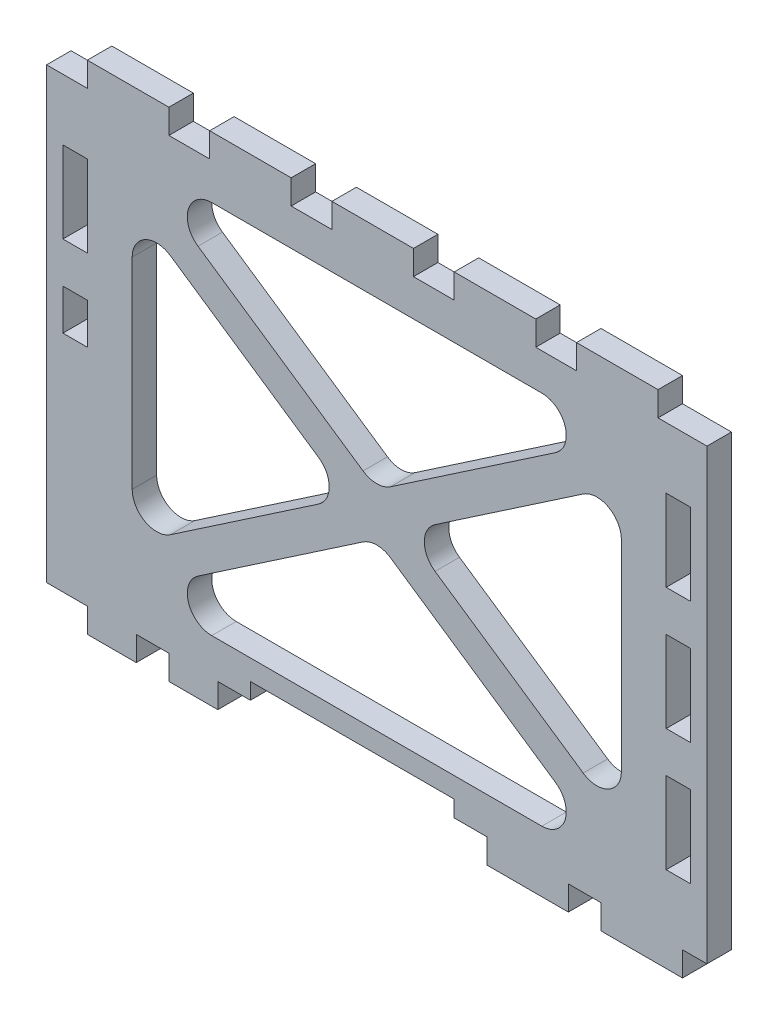
SolidWorks part; units mm, degrees
material "轻木"
ref_plane "前视基准面" through (0, 0, 0) normal (0, 0, 1) x (1, 0, 0)
ref_plane "上视基准面" through (0, 0, 0) normal (0, 1, 0) x (1, 0, 0)
ref_plane "右视基准面" through (0, 0, 0) normal (1, 0, 0) x (0, 0, -1)
sketch "草图1" plane through (0, 0, 0) normal (0, 0, 1) x (1, 0, 0)
  line L0 (-10.5, 27.5) -> (-10.5, 30.5)
  line L1 (-40.5, 27.5) -> (-35.5, 27.5)
  line L2 (-40.5, 27.5) -> (-40.5, -27.5)
  line L3 (-40.5, -27.5) -> (-35.5, -27.5)
  line L6 (35.5, 5) -> (35.5, -5)
  line L8 (-25.5, 27.5) -> (-25.5, 30.5)
  line L9 (-25.5, 30.5) -> (-35.5, 30.5)
  line L10 (-35.5, 27.5) -> (-35.5, 30.5)
  line L12 (-20.5, 27.5) -> (-20.5, 30.5)
  line L13 (-10.5, 30.5) -> (-20.5, 30.5)
  line L14 (4.5, 27.5) -> (4.5, 30.5)
  line L16 (-5.5, 27.5) -> (-5.5, 30.5)
  line L17 (4.5, 30.5) -> (-5.5, 30.5)
  line L18 (19.5, 27.5) -> (19.5, 30.5)
  line L20 (9.5, 27.5) -> (9.5, 30.5)
  line L21 (19.5, 30.5) -> (9.5, 30.5)
  line L22 (34.5, 27.5) -> (34.5, 30.5)
  line L24 (24.5, 27.5) -> (24.5, 30.5)
  line L25 (34.5, 30.5) -> (24.5, 30.5)
  line L26 (-25.5, -27.5) -> (-25.5, -30.5)
  line L28 (-35.5, -27.5) -> (-35.5, -30.5)
  line L29 (-35.5, -30.5) -> (-29.5, -30.5)
  line L30 (-29.5, -27.5) -> (-29.5, -30.5)
  line L32 (-19.5, -27.5) -> (-19.5, -30.5)
  line L33 (-25.5, -30.5) -> (-19.5, -30.5)
  line L34 (-15.5, -27.5) -> (-15.5, -25.5)
  line L35 (-15.5, -25.5) -> (9.5, -25.5)
  line L36 (9.5, -25.5) -> (9.5, -27.5)
  line L37 (27.5, -27.5) -> (27.5, -30.5)
  line L39 (13.5, -27.5) -> (13.5, -30.5)
  line L40 (13.5, -30.5) -> (23.5, -30.5)
  line L41 (23.5, -27.5) -> (23.5, -30.5)
  line L43 (37.5, -27.5) -> (37.5, -30.5)
  line L44 (27.5, -30.5) -> (37.5, -30.5)
  line L60 (9.5, -27.5) -> (13.5, -27.5)
  line L61 (-29.5, -27.5) -> (-25.5, -27.5)
  line L62 (-19.5, -27.5) -> (-15.5, -27.5)
  line L63 (-25.5, 27.5) -> (-20.5, 27.5)
  line L64 (-10.5, 27.5) -> (-5.5, 27.5)
  line L65 (4.5, 27.5) -> (9.5, 27.5)
  line L66 (19.5, 27.5) -> (24.5, 27.5)
  line L67 (34.5, 27.5) -> (40.5, 27.5)
  line L68 (23.5, -27.5) -> (27.5, -27.5)
  line L69 (37.5, -27.5) -> (40.5, -27.5)
  line L70 (35.5, 20) -> (38.5, 20)
  line L71 (35.5, 20) -> (35.5, 10)
  line L72 (35.5, 10) -> (38.5, 10)
  line L73 (38.5, 20) -> (38.5, 10)
  line L74 (35.5, 5) -> (38.5, 5)
  line L75 (38.5, 5) -> (38.5, -5)
  line L76 (35.5, -5) -> (38.5, -5)
  line L77 (35.5, -10) -> (35.5, -20)
  line L78 (35.5, -10) -> (38.5, -10)
  line L79 (38.5, -10) -> (38.5, -20)
  line L80 (35.5, -20) -> (38.5, -20)
  line L81 (40.5, 27.5) -> (40.5, -27.5)
  line L82 (0, -55) -> (0, 55) construction
  line L87 (-35.5, 5) -> (-38.5, 5)
  line L88 (-38.5, 5) -> (-38.5, 0)
  line L90 (-35.5, 5) -> (-35.5, 0)
  line L91 (-35.5, 10) -> (-38.5, 10)
  line L92 (-38.5, 20) -> (-38.5, 10)
  line L93 (-35.5, 20) -> (-38.5, 20)
  line L94 (-35.5, 20) -> (-35.5, 10)
  line L95 (-35.5, 0) -> (-38.5, 0)
  point P0 (0, 0)
  point P10 (-35.5, 29)
  dimension "D1" = 81
  dimension "D2" = 55
  dimension "D3" = 3
  dimension "D4" = 10
  dimension "D5" = 5
  dimension "D7" = 6
  dimension "D8" = 3
  dimension "D9" = 5
  dimension "D11" = 4
  dimension "D12" = 25
  dimension "D13" = 10
  dimension "D14" = 4
  dimension "D16" = 3
  dimension "D17" = 10
  dimension "D19" = 3
  dimension "D18" = 7.5
  dimension "D6" = 5
  dimension "D10" = 2
  dimension "D15" = 2
extrude "凸台-拉伸1" add sketch "草图1" along normal blind 3
sketch "草图2" plane through (0, 0, 3) normal (0, 0, 1) x (1, 0, 0)
  line L0 (40.5, 27.5) -> (-40.5, -27.5) construction
  line L1 (-40.5, 27.5) -> (40.5, -27.5) construction
  line L4 (-30, 23) -> (30, 23)
  line L5 (30, 23) -> (0, 2.6296)
  line L6 (-30, 23) -> (0, 2.6296)
  line L7 (1.65, 0) -> (-1.65, 0) construction
  line L8 (-30, -23) -> (0, -2.6296)
  line L9 (30, -23) -> (0, -2.6296)
  line L10 (-30, -23) -> (30, -23)
  line L12 (30, -18) -> (30, 18)
  line L13 (30, 18) -> (3.4909, 0)
  line L14 (30, -18) -> (3.4909, 0)
  line L15 (-30, -18) -> (-3.4909, 0)
  line L16 (-30, 18) -> (-3.4909, 0)
  line L17 (-30, -18) -> (-30, 18)
extrude "切除-拉伸1" cut sketch "草图2" against normal blind 10
fillet "圆角1" radius 3 12 edges at (-30, -23, 1.5) (0, -2.6296, 1.5) (30, -23, 1.5) (30, -18, 1.5) (3.4909, 0, 1.5) (30, 18, 1.5) (30, 23, 1.5) (-30, 23, 1.5) (0, 2.6296, 1.5) (-3.4909, 0, 1.5) (-30, -18, 1.5) (-30, 18, 1.5)
